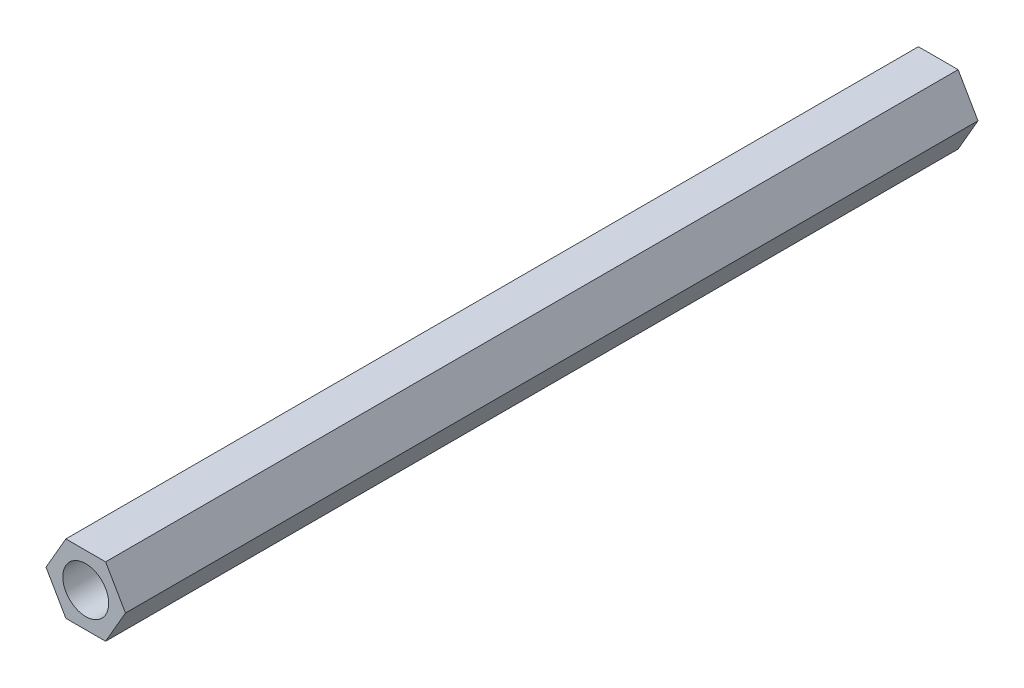
SolidWorks part; units mm, degrees
material "高铅黄铜，UNS C34200"
ref_plane "前视基准面" through (0, 0, 0) normal (0, 0, 1) x (1, 0, 0)
ref_plane "上视基准面" through (0, 0, 0) normal (0, 1, 0) x (1, 0, 0)
ref_plane "右视基准面" through (0, 0, 0) normal (1, 0, 0) x (0, 0, -1)
sketch "草图1" plane through (0, 0, 0) normal (0, 0, 1) x (1, 0, 0)
  line L1 (5.1962, 0) -> (2.5981, 4.5)
  line L2 (2.5981, 4.5) -> (-2.5981, 4.5)
  line L3 (-2.5981, 4.5) -> (-5.1962, 0)
  line L4 (-5.1962, 0) -> (-2.5981, -4.5)
  line L5 (-2.5981, -4.5) -> (2.5981, -4.5)
  line L6 (2.5981, -4.5) -> (5.1962, 0)
  circle A0 centre (0, 0) radius 3
  circle A1 centre (0, 0) radius 4.5 construction
extrude "凸台-拉伸1" add sketch "草图1" along normal blind 111.5
